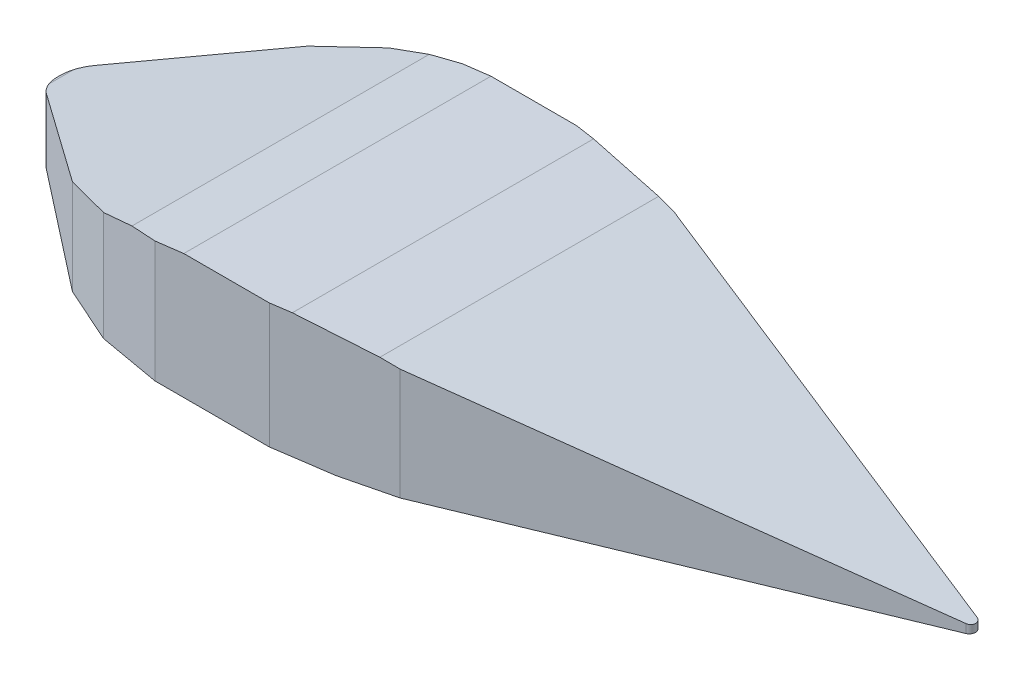
SolidWorks part; units mm, degrees
ref_plane "Front Plane" through (0, 0, 0) normal (0, 0, 1) x (1, 0, 0)
ref_plane "Top Plane" through (0, 0, 0) normal (0, 1, 0) x (1, 0, 0)
ref_plane "Right Plane" through (0, 0, 0) normal (1, 0, 0) x (0, 0, -1)
sketch "Sketch1" plane through (0, 0, 0) normal (0, 1, 0) x (1, 0, 0)
  line L0 (161.4098, 126.0887) -> (784.13, 612.54)
  line L1 (784.13, 612.54) -> (1076.464, 742.696)
  line L2 (1076.464, 742.696) -> (1401.451, 800)
  line L3 (1401.451, 800) -> (1997.019, 800)
  line L4 (1997.019, 800) -> (2590.582, 712.35)
  line L5 (2590.582, 712.35) -> (4854.8761, 28.7196)
  line L6 (4854.8761, -28.7196) -> (2590.582, -712.35)
  line L7 (2590.582, -712.35) -> (1997.019, -800)
  line L8 (1997.019, -800) -> (1401.451, -800)
  line L9 (1401.451, -800) -> (1076.464, -742.696)
  line L10 (1076.464, -742.696) -> (784.13, -612.54)
  line L11 (784.13, -612.54) -> (161.4098, -126.0887)
  arc A0 (161.4098, 126.0887) -> (161.4098, -126.0887) centre (259.9067, 0) ccw
  arc A1 (4854.8761, 28.7196) -> (4854.8761, -28.7196) centre (4846.2052, 0) cw
  point P15 (0, 0)
  point P18 (4950, 0)
  dimension "r0" = 160
  dimension "r6" = 30
  dimension "x1" = 784.13
  dimension "x2" = 1076.464
  dimension "x3" = 1401.451
  dimension "x4" = 1997.019
  dimension "x5" = 2590.582
  dimension "x6" = 4950
  dimension "x7" = 2590.582
  dimension "x8" = 1997.019
  dimension "x9" = 1401.451
  dimension "x10" = 1076.464
  dimension "x11" = 784.13
  dimension "y1" = 612.54
  dimension "y2" = 742.696
  dimension "y3" = 800
  dimension "y5" = 712.35
  dimension "y7" = 712.35
  dimension "y8" = 800
  dimension "y10" = 742.696
  dimension "y11" = 612.54
extrude "TopView_Extrude" add sketch "Sketch1" along normal blind 800
sketch "Sketch3" plane through (0, 0, 0) normal (0, 0, 1) x (1, 0, 0)
  line L0 (0, 300) -> (0, 332.8541)
  line L1 (113.6551, 478.3843) -> (1255.921, 763.655)
  line L2 (1255.921, 763.655) -> (1551.451, 800)
  line L3 (1551.451, 800) -> (2101.451, 800)
  line L4 (2101.451, 800) -> (2499.002, 768.799)
  line L5 (2499.002, 768.799) -> (4950, 381.685)
  line L6 (4950, 381.685) -> (4950, 359.158)
  line L7 (4950, 359.158) -> (2301.451, 150)
  line L8 (2301.451, 150) -> (150, 150)
  arc A0 (0, 300) -> (150, 150) centre (150, 300) ccw
  arc A1 (0, 332.8541) -> (113.6551, 478.3843) centre (150, 332.8541) cw
  point P12 (0, 150)
  point P15 (0, 450)
  dimension "r0" = 150
  dimension "r1" = 150
  dimension "x2" = 1255.921
  dimension "x3" = 1551.451
  dimension "x4" = 2101.451
  dimension "x5" = 2499.002
  dimension "x6" = 4950
  dimension "x8" = 2301.451
  dimension "y0" = 150
  dimension "y1" = 450
  dimension "y2" = 763.655
  dimension "y3" = 800
  dimension "y5" = 768.799
  dimension "y6" = 381.685
  dimension "y7" = 359.158
extrude "SideProfile_Cut" cut sketch "Sketch3" against normal through all and the other way through all flip side to cut
